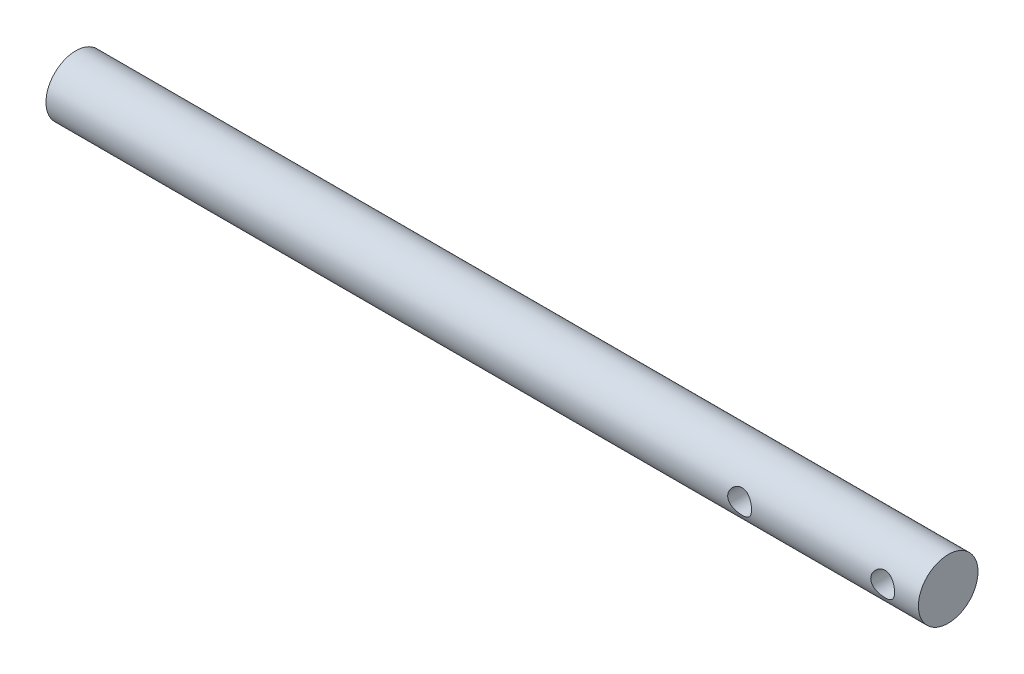
SolidWorks part; units mm, degrees
material "AISI 304"
ref_plane "Front Plane" through (0, 0, 0) normal (0, 0, 1) x (1, 0, 0)
ref_plane "Top Plane" through (0, 0, 0) normal (0, 1, 0) x (1, 0, 0)
ref_plane "Right Plane" through (0, 0, 0) normal (1, 0, 0) x (0, 0, -1)
sketch "Sketch1" plane through (0, 0, 0) normal (1, 0, 0) x (0, 0, -1)
  circle A0 centre (0, 0) radius 25
  dimension "D1" = 50
extrude "Boss-Extrude1" add sketch "Sketch1" along normal mid plane 732
sketch "Sketch2" plane through (0, 0, 0) normal (0, 0, 1) x (1, 0, 0)
  line L0 (366, -25) -> (366, 25) construction
  circle A0 centre (336, 0) radius 10
  circle A1 centre (216, 0) radius 10
  dimension "D1" = 20
  dimension "D2" = 20
  dimension "D3" = 30
  dimension "D4" = 150
extrude "Cut-Extrude1" cut sketch "Sketch2" against normal mid plane 320
